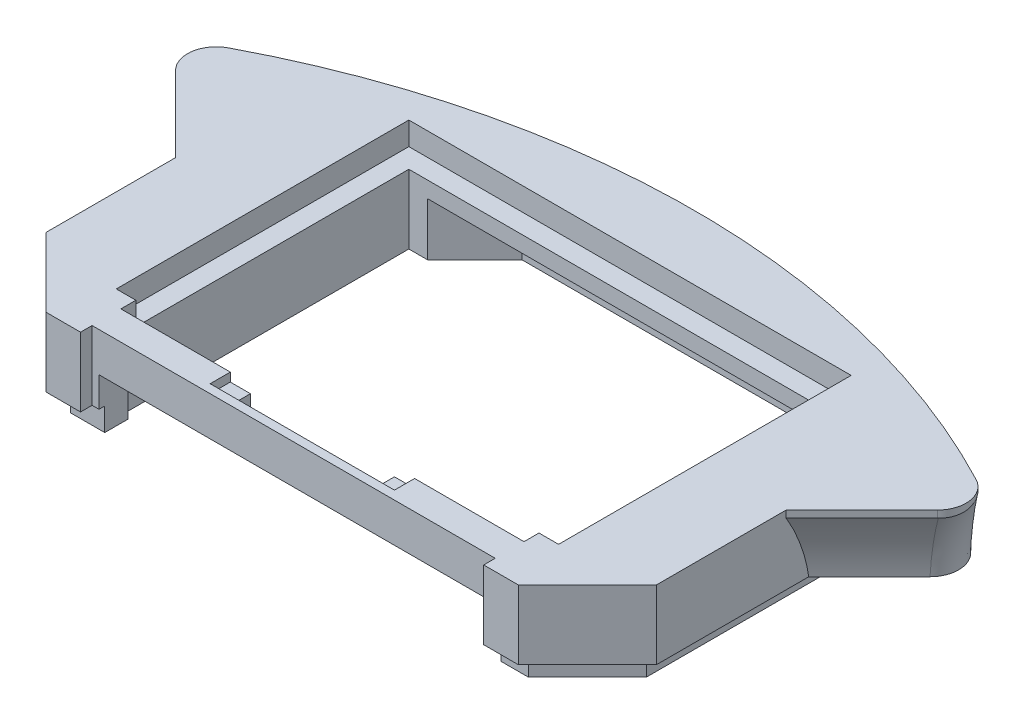
SolidWorks part; units mm, degrees
ref_plane "Front Plane" through (0, 0, 0) normal (0, 0, 1) x (1, 0, 0)
ref_plane "Top Plane" through (0, 0, 0) normal (0, 1, 0) x (1, 0, 0)
ref_plane "Right Plane" through (0, 0, 0) normal (1, 0, 0) x (0, 0, -1)
sketch "Sketch1" plane through (0, 0, 0) normal (0, 1, 0) x (1, 0, 0)
  line L0 (-53, 129.1478) -> (-53, 80)
  line L1 (-53, 80) -> (-41, 68)
  line L2 (-41, 68) -> (41, 68)
  line L3 (41, 68) -> (53, 80)
  line L4 (53, 80) -> (53, 129.1478)
  arc A0 (-53, 129.1478) -> (53, 129.1478) centre (0, 0) cw
  dimension "D1" = 139.6
  dimension "D2" = 68
  dimension "D3" = 80
  dimension "D4" = 135
  dimension "D5" = 53
  dimension "D6" = 106
extrude "Boss-Extrude1" add sketch "Sketch1" along normal blind 16
sketch "Sketch2" plane through (0, 0, 0) normal (0, -1, 0) x (1, 0, 0)
  line L0 (-33.8, -122.9657) -> (-33.8, -62.4)
  line L1 (-23.4, -132.8) -> (24.6, -132.8) construction
  line L2 (-33.4, -122.8) -> (-33.4, -62.8) construction
  line L3 (-33.4, -62.8) -> (34.6, -62.8) construction
  line L4 (34.6, -122.8) -> (34.6, -62.8) construction
  line L5 (-33.8, -62.4) -> (35, -62.4)
  line L6 (35, -122.9657) -> (35, -62.4)
  line L7 (24.7657, -133.2) -> (35, -122.9657)
  line L8 (-23.5657, -133.2) -> (24.7657, -133.2)
  line L9 (-33.8, -122.9657) -> (-23.5657, -133.2)
  line L10 (-33.4, -122.8) -> (-23.4, -132.8) construction
  line L12 (24.6, -132.8) -> (34.6, -122.8) construction
  dimension "D1" = 68
  dimension "D2" = 70
  dimension "D3" = 62.8
  dimension "D4" = 34.6
  dimension "D6" = 10
  dimension "D7" = 135
  dimension "D5" = 0.4
extrude "Cut-Extrude1" cut sketch "Sketch2" against normal offset from surface (9.2 mm away) 6.8 up to face at (0, 16, -94.1246)
sketch "Sketch3" plane through (0, 16, 0) normal (0, 1, 0) x (1, 0, 0)
  line L1 (-35, 125) -> (35, 125)
  line L2 (-35, 125) -> (-35, 75)
  line L3 (-35, 75) -> (35, 75)
  line L4 (35, 125) -> (35, 75)
  dimension "D1" = 75
  dimension "D2" = 70
  dimension "D3" = 50
  dimension "D4" = 35
extrude "Cut-Extrude2" cut sketch "Sketch3" against normal up to next
sketch "Sketch7" plane through (0, 0, 0) normal (0, -1, 0) x (1, 0, 0)
  line L41 (-50, -81.2426) -> (-50, -127.1203)
  line L42 (50, -127.1203) -> (50, -81.2426)
  line L43 (50, -81.2426) -> (39.7574, -71)
  line L44 (39.7574, -71) -> (35, -71)
  line L45 (-33.8, -71) -> (-39.7574, -71)
  line L46 (35, -71) -> (-33.8, -71)
  line L47 (-39.7574, -71) -> (-50, -81.2426)
  line L48 (-50, -81.2426) -> (-50, -127.1203)
  line L49 (50, -127.1203) -> (50, -81.2426)
  line L50 (50, -81.2426) -> (39.7574, -71)
  line L51 (39.7574, -71) -> (35, -71)
  line L52 (-33.8, -71) -> (-39.7574, -71)
  line L53 (35, -71) -> (-33.8, -71)
  line L54 (-39.7574, -71) -> (-50, -81.2426)
  arc A3 (-50, -127.1203) -> (50, -127.1203) centre (0, 0) ccw
  arc A4 (-50, -127.1203) -> (50, -127.1203) centre (0, 0) ccw
  dimension "D1" = 3
extrude "Cut-Extrude5" cut sketch "Sketch7" against normal blind 4 flip side to cut
sketch "Sketch8" plane through (0, 16, 0) normal (0, 1, 0) x (1, 0, 0)
  line L0 (70.8106, 120.308) -> (53, 102.4975)
  line L2 (0, 0) -> (95.9331, 95.9331) construction
  line L3 (53, 129.1478) -> (53, 102.4975)
  line L4 (53, 80) -> (53, 129.1478) construction
  arc A0 (53, 129.1478) -> (70.8106, 120.308) centre (0, 0) cw
  arc A2 (53, 129.1478) -> (-53, 129.1478) centre (0, 0) ccw construction
  dimension "D1" = 45
  dimension "D2" = 35
extrude "Boss-Extrude3" add sketch "Sketch8" against normal up to surface (12 mm away) up to face at (0.15, 4, -88.1846)
ref_plane "Plane1" through (95.5593, 0, -95.5593) normal (-0.7071, 0, 0.7071) x (0, 1, 0)
mirror "Mirror1" about plane through (0, 0, 0) normal (1, 0, 0) of "Boss-Extrude3"
sketch "Sketch9" plane through (95.5593, 0, -95.5593) normal (-0.7071, 0, 0.7071) x (0, 1, 0)
  line L0 (4, 35) -> (16, 35) construction
  line L1 (16, 19.0919) -> (16, 35) construction
  circle A0 centre (0, 0) radius 38
  dimension "D1" = 76
  dimension "D2" = 35
  dimension "D3" = 16
extrude "Cut-Extrude7" cut sketch "Sketch9" along normal up to surface (98.1879 mm away)
ref_plane "Plane2" through (-95.5593, 0, -95.5593) normal (0.7071, 0, 0.7071) x (0, 1, 0)
sketch "Sketch10" plane through (-95.5593, 0, -95.5593) normal (0.7071, 0, 0.7071) x (0, 1, 0)
  line L0 (16, -135.1413) -> (16, -35) construction
  line L1 (4, -35) -> (16, -35) construction
  circle A0 centre (0, 0) radius 38
  dimension "D1" = 76
  dimension "D2" = 16
  dimension "D3" = 35
extrude "Cut-Extrude8" cut sketch "Sketch10" along normal up to surface (22.1879 mm away)
fillet "Fillet1" radius 5 4 edges at (70.8106, 15.3993, -120.308) (-70.8106, 15.3993, -120.308)
sketch "Sketch12" plane through (0, 16, 0) normal (0, 1, 0) x (1, 0, 0)
  line L0 (-35, 75) -> (35, 75) construction
  line L1 (-12.5, 71.5) -> (12.5, 71.5)
  line L2 (-12.5, 71.5) -> (-12.5, 75)
  line L3 (-12.5, 75) -> (12.5, 75)
  line L4 (12.5, 71.5) -> (12.5, 75)
  dimension "D1" = 71.5
  dimension "D2" = 25
  dimension "D3" = 12.5
extrude "Cut-Extrude10" cut sketch "Sketch12" against normal blind 4
sketch "Sketch13" plane through (0, 16, 0) normal (0, 1, 0) x (1, 0, 0)
  line L0 (12.5, 71.5) -> (12.5, 75) construction
  line L1 (-12.5, 75) -> (-16, 75)
  line L2 (-12.5, 75) -> (-12.5, 71.5)
  line L3 (-12.5, 71.5) -> (-16, 71.5)
  line L4 (-16, 75) -> (-16, 71.5)
  line L5 (12.5, 75) -> (16, 75)
  line L6 (12.5, 75) -> (12.5, 71.5)
  line L7 (12.5, 71.5) -> (16, 71.5)
  line L8 (16, 75) -> (16, 71.5)
extrude "Cut-Extrude11" cut sketch "Sketch13" against normal blind 1.5
sketch "Sketch14" plane through (0, 16, 0) normal (0, 1, 0) x (1, 0, 0)
  line L0 (-41, 68) -> (41, 68) construction
  line L1 (-35, 68) -> (35, 68)
  line L2 (-35, 68) -> (-35, 70)
  line L3 (-35, 70) -> (35, 70)
  line L4 (35, 68) -> (35, 70)
  line L5 (-35, 125) -> (-35, 75) construction
  line L6 (35, 75) -> (35, 125) construction
  dimension "D1" = 2
extrude "Cut-Extrude12" cut sketch "Sketch14" against normal up to next
sketch "Sketch15" plane through (0, 16, 0) normal (0, 1, 0) x (1, 0, 0)
  line L0 (-35, 77.6) -> (-35, 125)
  line L1 (-35, 125) -> (35, 125)
  line L2 (35, 125) -> (35, 77.6)
  line L3 (35, 77.6) -> (38.4, 77.6)
  line L5 (38.4, 77.6) -> (38.4, 128.4)
  line L6 (38.4, 128.4) -> (-38.4, 128.4)
  line L7 (-38.4, 128.4) -> (-38.4, 77.6)
  line L9 (-38.4, 77.6) -> (-35, 77.6)
  line L10 (35, 75) -> (35, 125) construction
  line L11 (-41, 68) -> (-35, 68) construction
  dimension "D1" = 3.4
  dimension "D2" = 3.4
  dimension "D3" = 9.6
extrude "Cut-Extrude13" cut sketch "Sketch15" against normal blind 4
